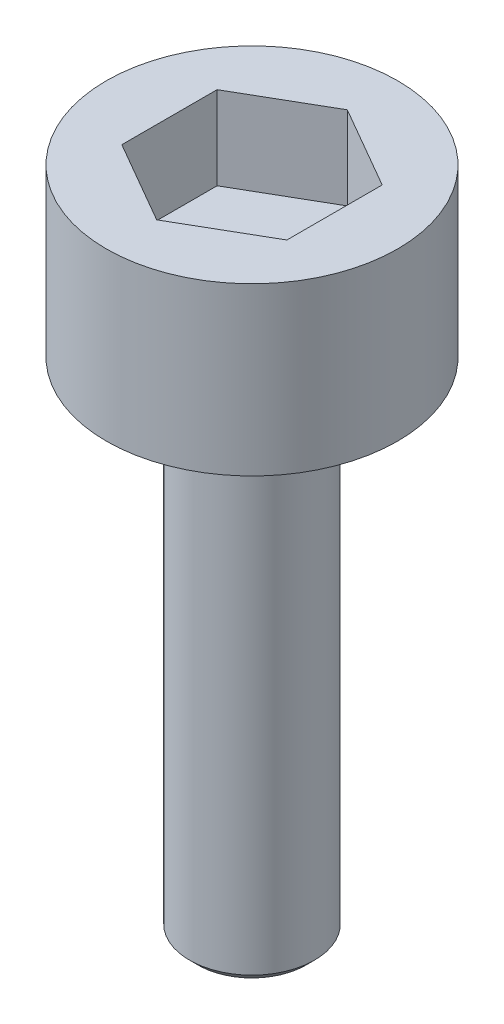
SolidWorks part; units mm, degrees
ref_plane "Alzado" through (0, 0, 0) normal (0, 0, 1) x (1, 0, 0)
ref_plane "Planta" through (0, 0, 0) normal (0, 1, 0) x (1, 0, 0)
ref_plane "Vista lateral" through (0, 0, 0) normal (1, 0, 0) x (0, 0, -1)
sketch "Croquis1" plane through (0, 0, 0) normal (0, 1, 0) x (1, 0, 0)
  circle A0 centre (0, 0) radius 3.5
  dimension "D1" = 7
extrude "Saliente-Extruir1" add sketch "Croquis1" along normal blind 4
sketch "Croquis2" plane through (0, 0, 0) normal (0, -1, 0) x (1, 0, 0)
  circle A0 centre (0, 0) radius 1.5
  dimension "D1" = 3
extrude "Saliente-Extruir2" add sketch "Croquis2" along normal blind 12
chamfer "Chaflán1" distance 0.2 angle 45 1 edges at (0, -12, -1.5)
sketch "Croquis3" plane through (0, 4, 0) normal (0, 1, 0) x (1, 0, 0)
  line L1 (0, 2.2897) -> (-1.9829, 1.1448)
  line L2 (-1.9829, 1.1448) -> (-1.9829, -1.1448)
  line L3 (-1.9829, -1.1448) -> (0, -2.2897)
  line L4 (0, -2.2897) -> (1.9829, -1.1448)
  line L5 (1.9829, -1.1448) -> (1.9829, 1.1448)
  line L6 (1.9829, 1.1448) -> (0, 2.2897)
  circle A0 centre (0, 0) radius 1.9829 construction
extrude "Cortar-Extruir1" cut sketch "Croquis3" against normal blind 2
